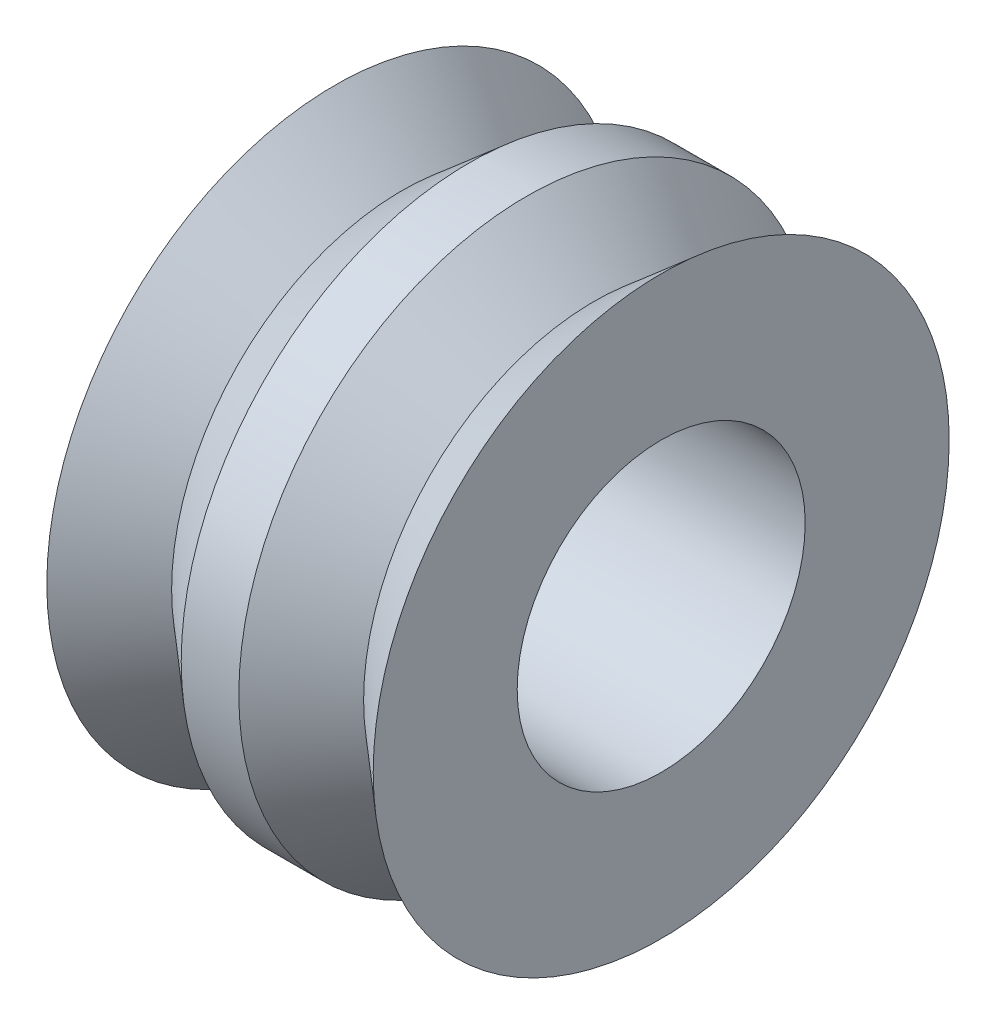
SolidWorks part; units mm, degrees
ref_plane "Vorne" through (0, 0, 0) normal (0, 0, 1) x (1, 0, 0)
ref_plane "Oben" through (0, 0, 0) normal (0, 1, 0) x (1, 0, 0)
ref_plane "Rechts" through (0, 0, 0) normal (1, 0, 0) x (0, 0, -1)
ref_plane "E_Boden" through (0, 1, 0) normal (0, 1, 0) x (1, 0, 0)
sketch "Skizze1" plane through (0, 0, 0) normal (0, 0, 1) x (1, 0, 0)
  line L0 (-85.1913, 0) -> (91.0931, 0) construction
  line L1 (0, 0) -> (0, 44.7767) construction
  line L2 (0, 44.7767) -> (0, -54.7842) construction
  line L3 (-8.5, 0) -> (-8.5, 15)
  line L4 (-8.5, 15) -> (-5, 12)
  line L5 (-5, 12) -> (-1.5, 15)
  line L6 (-1.5, 15) -> (1.5, 15)
  line L7 (1.5, 15) -> (5, 12)
  line L8 (5, 12) -> (8.5, 15)
  line L9 (8.5, 15) -> (8.5, 0)
  line L10 (-8.5, 0) -> (8.5, 0)
  dimension "D1" = 15
  dimension "D2" = 7
  dimension "D3" = 7
  dimension "D4" = 3
  dimension "D5" = 3.5
  dimension "D6" = 3.5
  dimension "D7" = 3
  dimension "D8" = 3
  dimension "D9" = 15
revolve "Rotation1" add sketch "Skizze1" angle 360 about L0
hole_wizard "Ø15.0 (15) Durchmesser Bohrung2" positions "Skizze4" profile "Skizze5" hole size "Ø15.0" standard "DIN" end condition through all
sketch "Skizze4" plane through (-8.5, 0, 0) normal (-1, 0, 0) x (0, 0, 1)
  point P0 (0, 0)
sketch "Skizze5" plane through (-8.5, 0, 0) normal (0, 1, 0) x (0, 0, 1)
  line L0 (0, 0) -> (0, 17)
  line L1 (0, 17) -> (7.5, 17)
  line L2 (7.5, 17) -> (7.5, 0)
  line L5 (7.5, 0) -> (0, 0)
  line L11 (0, -6.35) -> (0, 107.95) construction
  dimension "Bohrerdurchmesser" = 15
  dimension "Bohrungstiefe" = 17
